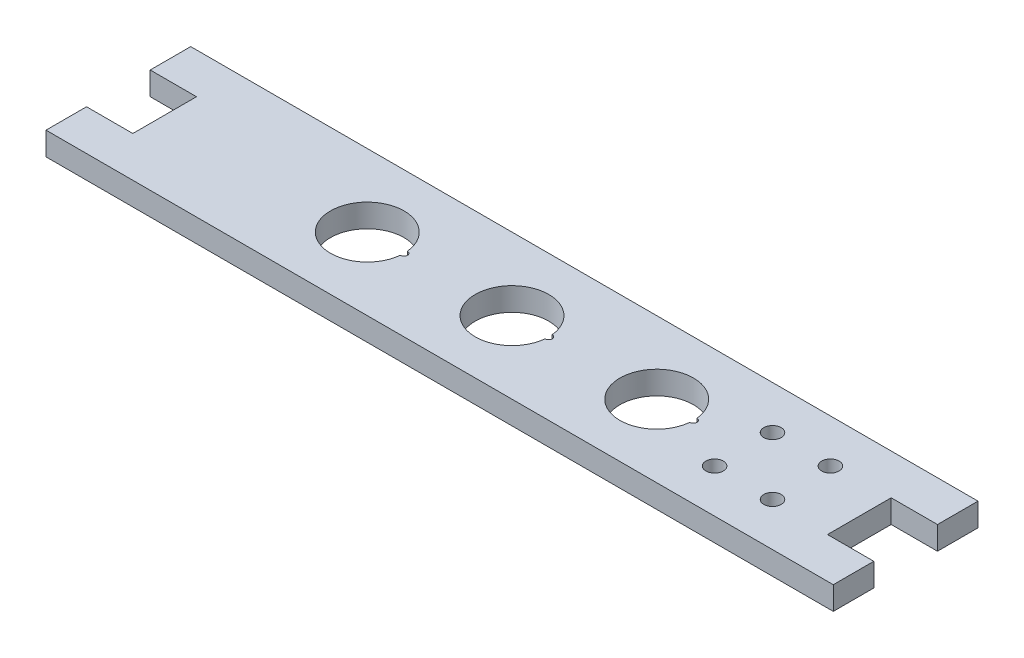
SolidWorks part; units mm, degrees
ref_plane "Front Plane" through (0, 0, 0) normal (0, 0, 1) x (1, 0, 0)
ref_plane "Top Plane" through (0, 0, 0) normal (0, 1, 0) x (1, 0, 0)
ref_plane "Right Plane" through (0, 0, 0) normal (1, 0, 0) x (0, 0, -1)
sketch "Sketch1" plane through (0, 0, 0) normal (0, 1, 0) x (1, 0, 0)
  line L0 (-69.7192, 0) -> (78.5805, 0) construction
  line L1 (-60, 12.5) -> (60, 12.5)
  line L2 (-60, 12.5) -> (-60, -12.5)
  line L3 (-60, -12.5) -> (60, -12.5)
  line L4 (60, 12.5) -> (60, -12.5)
  circle A0 centre (25, 0) radius 6.35 construction
  arc A1 (31.3217, 0.5993) -> (31.3217, -0.5993) centre (31.35, 0) cw
  arc A2 (31.3217, 0.5993) -> (31.3217, -0.5993) centre (25, 0) ccw
  arc A3 (6.3217, 0.5993) -> (6.3217, -0.5993) centre (6.35, 0) cw
  arc A4 (6.3217, 0.5993) -> (6.3217, -0.5993) centre (0, 0) ccw
  arc A5 (-18.6783, 0.5993) -> (-18.6783, -0.5993) centre (-18.65, 0) cw
  arc A6 (-18.6783, 0.5993) -> (-18.6783, -0.5993) centre (-25, 0) ccw
  circle A7 centre (40, 5) radius 1.5
  circle A8 centre (40, -5) radius 1.5
  circle A9 centre (50, 5) radius 1.5
  circle A10 centre (50, -5) radius 1.5
  point P4 (0, 12.5)
  point P6 (60, 0)
  point P24 (-60, 0)
  dimension "D3" = 12.7
  dimension "D4" = 0.6
  dimension "D7" = 3
  dimension "D1" = 120
  dimension "D2" = 25
  dimension "D6" = 25
  dimension "D8" = 10
  dimension "D9" = 20
  dimension "D5" = 3
  dimension "D10" = 2
extrude "Boss-Extrude1" add sketch "Sketch1" along normal blind 4
sketch "Sketch2" plane through (-60, 0, 0) normal (-1, 0, 0) x (0, 0, 1)
  line L0 (-12.5, 4) -> (-12.5, 0) construction
  line L1 (-12.5, 0) -> (-5.5, 0)
  line L2 (-12.5, 0) -> (-12.5, 4)
  line L3 (-12.5, 4) -> (-5.5, 4)
  line L4 (-5.5, 0) -> (-5.5, 4)
  line L5 (-12.5, 0) -> (12.5, 0) construction
  line L6 (0, 10.2628) -> (0, -4.8201) construction
  line L7 (5.5, 0) -> (5.5, 4)
  line L8 (12.5, 4) -> (5.5, 4)
  line L9 (12.5, 0) -> (12.5, 4)
  line L10 (12.5, 0) -> (5.5, 0)
  dimension "D1" = 7
extrude "Boss-Extrude2" add sketch "Sketch2" along normal blind 8
ref_plane "Plane1" through (0, 0, 0) normal (-1, 0, 0) x (0, 0, 1)
mirror "Mirror1" about plane through (0, 0, 0) normal (-1, 0, 0) of "Boss-Extrude2"
